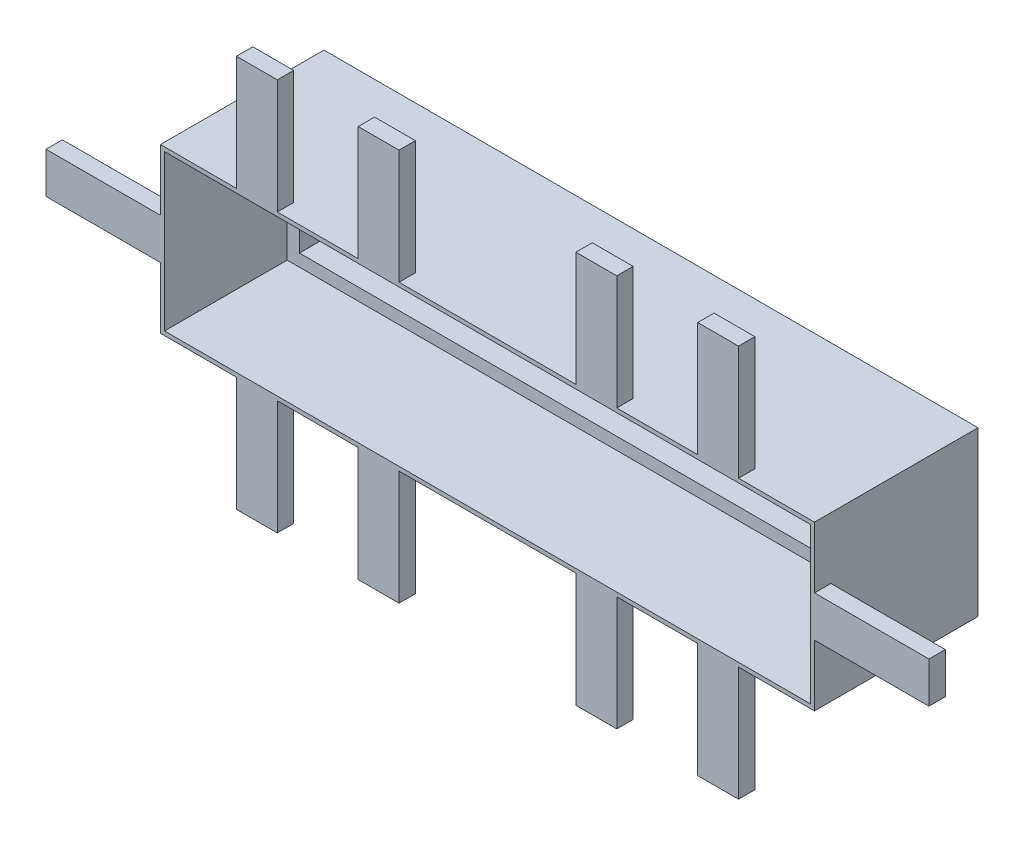
SolidWorks part; units mm, degrees
ref_plane "Plan de face" through (0, 0, 0) normal (0, 0, 1) x (1, 0, 0)
ref_plane "Plan de dessus" through (0, 0, 0) normal (0, 1, 0) x (1, 0, 0)
ref_plane "Plan de droite" through (0, 0, 0) normal (1, 0, 0) x (0, 0, -1)
sketch "Esquisse1" plane through (0, 0, 0) normal (0, 0, 1) x (1, 0, 0)
  line L1 (-200, 50) -> (200, 50)
  line L2 (-200, 50) -> (-200, -50)
  line L3 (-200, -50) -> (200, -50)
  line L4 (200, 50) -> (200, -50)
  line L5 (-200, 50) -> (200, -50) construction
  line L6 (-200, -50) -> (200, 50) construction
  line L7 (-197.5, 47.5) -> (197.5, 47.5)
  line L8 (-197.5, 47.5) -> (-197.5, -47.5)
  line L9 (-197.5, -47.5) -> (197.5, -47.5)
  line L10 (197.5, 47.5) -> (197.5, -47.5)
  line L11 (-197.5, 47.5) -> (197.5, -47.5) construction
  line L12 (-197.5, -47.5) -> (197.5, 47.5) construction
  point P0 (0, 0)
  point P6 (0, 0)
  dimension "D1" = 95
  dimension "D2" = 100
  dimension "D3" = 400
  dimension "D4" = 395
extrude "Boss.-Extru.2" add sketch "Esquisse1" along normal blind 100
sketch "Esquisse3" plane through (0, 0, 0) normal (0, 0, 1) x (1, 0, 0)
  line L1 (-200, 50) -> (200, 50)
  line L2 (-200, 50) -> (-200, -50)
  line L3 (-200, -50) -> (200, -50)
  line L4 (200, 50) -> (200, -50)
  line L5 (-200, 50) -> (200, -50) construction
  line L6 (-200, -50) -> (200, 50) construction
  line L7 (-190, 40) -> (190, 40)
  line L8 (-190, 40) -> (-190, -40)
  line L9 (-190, -40) -> (190, -40)
  line L10 (190, 40) -> (190, -40)
  line L11 (-190, 40) -> (190, -40) construction
  line L12 (-190, -40) -> (190, 40) construction
  point P0 (0, 0)
  point P6 (0, 0)
  dimension "D1" = 400
  dimension "D2" = 100
  dimension "D3" = 380
  dimension "D4" = 80
extrude "Boss.-Extru.3" add sketch "Esquisse3" along normal blind 25
sketch "Esquisse4" plane through (0, 0, 0) normal (0, 0, 1) x (1, 0, 0)
  line L0 (0, 0) -> (-200, 0) construction
  line L1 (-200, 50) -> (-200, -50) construction
  line L2 (0, 0) -> (0, 50) construction
  line L3 (200, 50) -> (-200, 50) construction
  line L4 (-200, 12.5) -> (-200, -12.5)
  line L5 (-270, 12.5) -> (-200, 12.5)
  line L6 (-270, 12.5) -> (-270, -12.5)
  line L7 (-270, -12.5) -> (-200, -12.5)
  line L9 (-270, 12.5) -> (-200, 0) construction
  line L10 (-270, -12.5) -> (-200, 0) construction
  line L11 (270, -12.5) -> (200, 0) construction
  line L12 (270, 12.5) -> (200, 0) construction
  line L13 (270, -12.5) -> (200, -12.5)
  line L14 (270, 12.5) -> (270, -12.5)
  line L15 (270, 12.5) -> (200, 12.5)
  line L16 (200, 12.5) -> (200, -12.5)
  line L17 (-153.5371, 50) -> (-128.5371, 50)
  line L18 (-153.5371, 120) -> (-128.5371, 120)
  line L19 (-153.5371, 120) -> (-153.5371, 50)
  line L21 (-128.5371, 120) -> (-128.5371, 50)
  line L22 (-153.5371, 120) -> (-141.0371, 50) construction
  line L23 (153.5371, 120) -> (153.5371, 50)
  line L24 (-79.0835, 120) -> (-54.0835, 120)
  line L25 (-79.0835, 120) -> (-79.0835, 50)
  line L27 (-54.0835, 120) -> (-54.0835, 50)
  line L28 (-79.0835, 120) -> (-66.5835, 50) construction
  line L29 (-66.5835, 50) -> (-54.0835, 120) construction
  line L30 (-79.0835, 50) -> (-54.0835, 50)
  line L31 (153.5371, 50) -> (128.5371, 50)
  line L32 (-141.0371, 50) -> (-128.5371, 120) construction
  line L33 (128.5371, 120) -> (128.5371, 50)
  line L34 (79.0835, 120) -> (79.0835, 50)
  line L35 (79.0835, 50) -> (54.0835, 50)
  line L36 (54.0835, 120) -> (54.0835, 50)
  line L37 (79.0835, 120) -> (54.0835, 120)
  line L38 (153.5371, 120) -> (128.5371, 120)
  line L39 (153.5371, -120) -> (128.5371, -120)
  line L40 (128.5371, -120) -> (128.5371, -50)
  line L41 (153.5371, -50) -> (128.5371, -50)
  line L42 (153.5371, -120) -> (153.5371, -50)
  line L43 (79.0835, -120) -> (54.0835, -120)
  line L44 (54.0835, -120) -> (54.0835, -50)
  line L45 (79.0835, -50) -> (54.0835, -50)
  line L46 (79.0835, -120) -> (79.0835, -50)
  line L47 (-54.0835, -120) -> (-54.0835, -50)
  line L48 (-79.0835, -50) -> (-54.0835, -50)
  line L49 (-79.0835, -120) -> (-54.0835, -120)
  line L50 (-79.0835, -120) -> (-79.0835, -50)
  line L51 (-153.5371, -50) -> (-128.5371, -50)
  line L52 (-153.5371, -120) -> (-128.5371, -120)
  line L53 (-128.5371, -120) -> (-128.5371, -50)
  line L54 (-153.5371, -120) -> (-153.5371, -50)
  point P14 (-141.0371, 50)
  point P22 (-66.5835, 50)
  point P31 (-66.5835, 120)
  dimension "D1" = 70
  dimension "D2" = 25
  dimension "D3" = 25
  dimension "D4" = 70
  dimension "D5" = 70
  dimension "D6" = 25
extrude "Boss.-Extru.4" add sketch "Esquisse4" against normal blind 10 from offset 100
